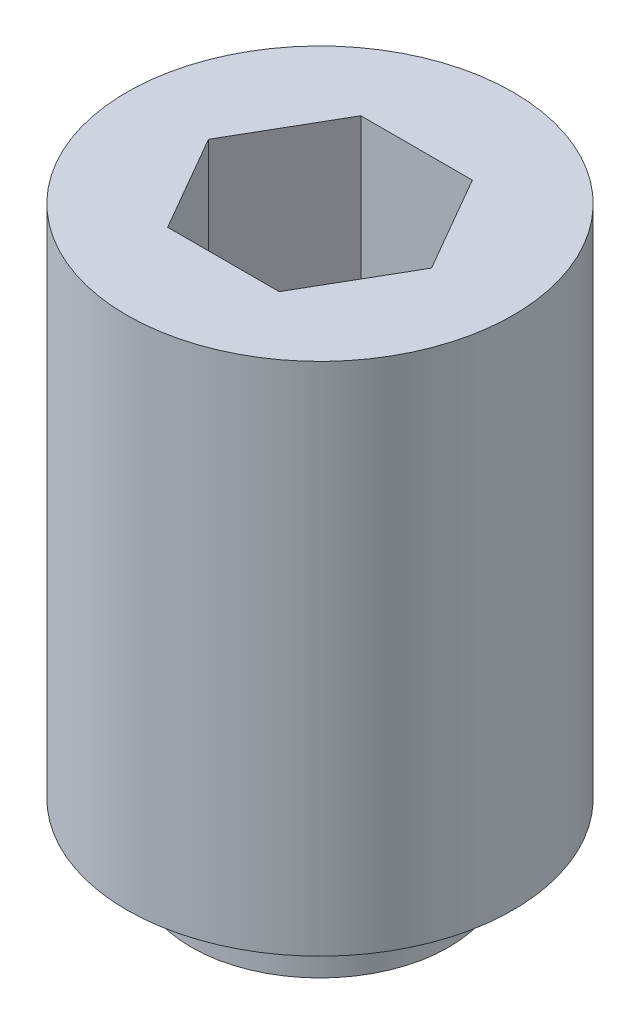
SolidWorks part; units mm, degrees
material "Plain Carbon Steel"
ref_plane "Front Plane" through (0, 0, 0) normal (0, 0, 1) x (1, 0, 0)
ref_plane "Top Plane" through (0, 0, 0) normal (0, 1, 0) x (1, 0, 0)
ref_plane "Right Plane" through (0, 0, 0) normal (1, 0, 0) x (0, 0, -1)
sketch "Sketch1" plane through (0, 0, 0) normal (0, 0, 1) x (1, 0, 0)
  line L0 (0, 61.6916) -> (0, -59.3578) construction
  line L1 (0, -8) -> (3, -8)
  line L2 (3, -8) -> (3, 0)
  line L3 (3, 0) -> (0, 0)
  line L6 (0, 0) -> (0, -8)
  dimension "L" = 8
  dimension "M" = 6
revolve "Revolve1" add sketch "Sketch1" angle 360 about L0
cosmetic thread "Cosmetic Thread1" parameters "D2"=5
sketch "Sketch2" plane through (0, 0, 0) normal (0, 1, 0) x (-1, 0, 0)
  line L1 (-0.866, -1.5) -> (0.866, -1.5)
  line L2 (0.866, -1.5) -> (1.7321, 0)
  line L3 (1.7321, 0) -> (0.866, 1.5)
  line L4 (0.866, 1.5) -> (-0.866, 1.5)
  line L5 (-0.866, 1.5) -> (-1.7321, 0)
  line L6 (-1.7321, 0) -> (-0.866, -1.5)
  circle A0 centre (0, 0) radius 1.5 construction
  dimension "B" = 3
sketch "Sketch3" plane through (0, -8, 0) normal (0, -1, 0) x (1, 0, 0)
  circle A0 centre (0, 0) radius 2
  dimension "d" = 4
extrude "Boss-Extrude1" add sketch "Sketch3" along normal blind 1 separate body
extrude "Cut-Extrude1" cut sketch "Sketch2" against normal blind 3.5
